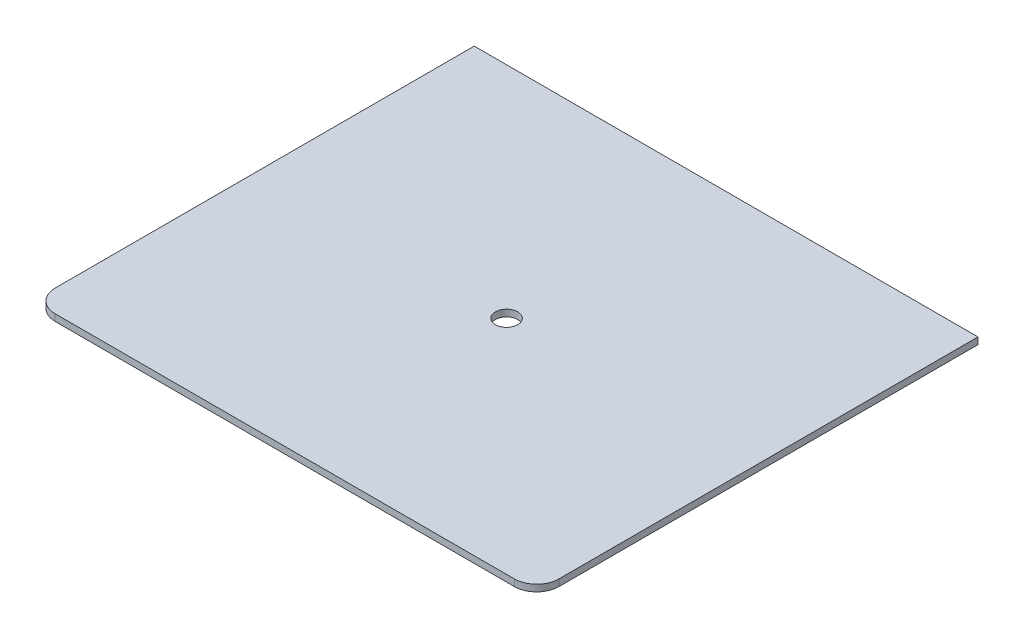
SolidWorks part; units mm, degrees
ref_plane "Front Plane" through (0, 0, 0) normal (0, 0, 1) x (1, 0, 0)
ref_plane "Top Plane" through (0, 0, 0) normal (0, 1, 0) x (1, 0, 0)
ref_plane "Right Plane" through (0, 0, 0) normal (1, 0, 0) x (0, 0, -1)
sketch "Sketch1" plane through (0, 0, 0) normal (0, 1, 0) x (1, 0, 0)
  line L1 (0, 0) -> (226, 0)
  line L2 (0, 0) -> (0, 198)
  line L3 (0, 198) -> (226, 198)
  line L4 (226, 0) -> (226, 198)
  dimension "D1" = 226
  dimension "D2" = 198
extrude "Boss-Extrude1" add sketch "Sketch1" along normal blind 3
sketch "Input for speaker" plane through (0, 3, 0) normal (0, 1, 0) x (1, 0, 0)
  line L0 (5, 198) -> (5, 1) construction
  line L1 (226, 198) -> (0, 198) construction
  line L3 (221, 198) -> (221, 1) construction
  line L4 (5, 1) -> (221, 1) construction
  line L7 (113, 198) -> (113, 1) construction
  line L8 (113, 99.5) -> (5, 99.5) construction
  line L9 (113, 99.5) -> (221, 99.5) construction
  line L10 (0, 0) -> (226, 0) construction
  line L11 (0, 198) -> (0, 0) construction
  circle A0 centre (113, 99.5) radius 5
  dimension "D3" = 10
  dimension "D1" = 1
  dimension "D2" = 5
extrude "Cut-Extrude1" cut sketch "Input for speaker" against normal blind 10 contours A0
fillet "Fillet1" radius 10 2 edges at (0, 1.5, 0) (226, 1.5, 0)
